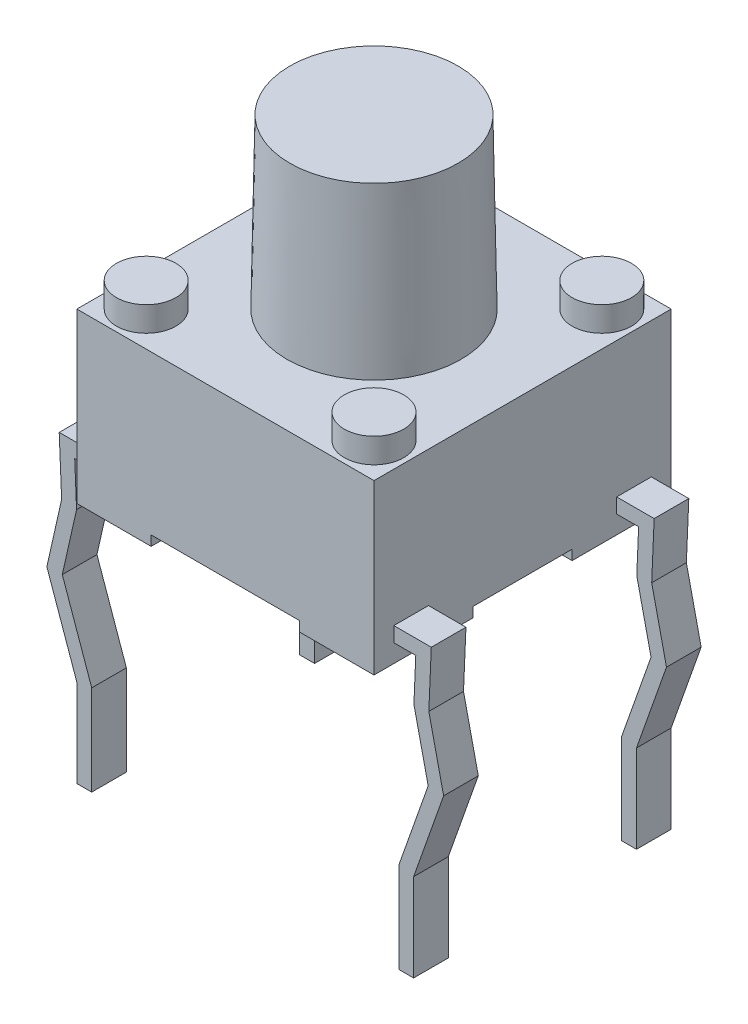
SolidWorks part; units mm, degrees
ref_plane "Ön Düzlem" through (0, 0, 0) normal (0, 0, 1) x (1, 0, 0)
ref_plane "Üst Düzlem" through (0, 0, 0) normal (0, 1, 0) x (1, 0, 0)
ref_plane "Sağ Düzlem" through (0, 0, 0) normal (1, 0, 0) x (0, 0, -1)
sketch "Çizim1" plane through (0, 0, 0) normal (0, 1, 0) x (1, 0, 0)
  line L1 (3, 3) -> (-3, 3)
  line L2 (3, 3) -> (3, -3)
  line L3 (3, -3) -> (-3, -3)
  line L4 (-3, 3) -> (-3, -3)
  line L5 (3, 3) -> (-3, -3) construction
  line L6 (3, -3) -> (-3, 3) construction
  point P0 (0, 0)
  dimension "D1" = 6
  dimension "D2" = 6
extrude "Yükseklik-Ekstrüzyon1" add sketch "Çizim1" against normal blind 3.3
sketch "Çizim2" plane through (0, 0, 0) normal (0, 1, 0) x (1, 0, 0)
  line L0 (-3, -3) -> (3, -3) construction
  line L1 (3, -3) -> (3, 3) construction
  line L2 (3, 3) -> (-3, 3) construction
  line L3 (-3, 3) -> (-3, -3) construction
  line L4 (-3, -3) -> (3, -3)
  line L5 (3, -3) -> (3, 3)
  line L6 (3, 3) -> (-3, 3)
  line L7 (-3, 3) -> (-3, -3)
extrude "Yükseklik-Ekstrüzyon2" add sketch "Çizim2" along normal blind 0.1
sketch "Çizim3" plane through (0, 0, 3) normal (0, 0, 1) x (1, 0, 0)
  line L0 (0, 0.1) -> (0, -3.3) construction
  line L1 (-3, 0.1) -> (3, 0.1) construction
  line L2 (-3, -3.3) -> (3, -3.3) construction
  line L3 (1.5, -3.1) -> (-1.5, -3.1)
  line L4 (-1.5, -3.1) -> (-1.5, -3.3)
  line L5 (-1.5, -3.3) -> (1.5, -3.3)
  line L6 (1.5, -3.3) -> (1.5, -3.1)
  point P9 (0, -3.1)
  dimension "D1" = 3
  dimension "D2" = 0.2
extrude "Kes-Ekstrüzyon1" cut sketch "Çizim3" against normal blind 1.5
mirror "Aynalama1" about plane through (0, 0, 0) normal (0, 0, 1) of "Kes-Ekstrüzyon1"
sketch "Çizim4" plane through (-3, 0, 0) normal (-1, 0, 0) x (0, 0, 1)
  line L0 (0, 0.1) -> (0, -3.3) construction
  line L1 (-3, 0.1) -> (3, 0.1) construction
  line L2 (-3, -3.3) -> (3, -3.3) construction
  line L3 (1, -3.1) -> (-1, -3.1)
  line L4 (-1, -3.1) -> (-1, -3.3)
  line L5 (-1, -3.3) -> (1, -3.3)
  line L6 (1, -3.3) -> (1, -3.1)
  point P9 (0, -3.1)
  dimension "D1" = 2
  dimension "D2" = 0.2
extrude "Kes-Ekstrüzyon2" cut sketch "Çizim4" against normal through all
sketch "Çizim5" plane through (0, 0.1, 0) normal (0, 1, 0) x (1, 0, 0)
  circle A0 centre (0, 0) radius 1.7
  dimension "D1" = 3.4
extrude "Yükseklik-Ekstrüzyon3" add sketch "Çizim5" along normal blind 3.4
draft "Draft4" type of draft neutral plane draft angle 1 faces to draft 1 face at (0, 3.5, 1.7) neutral plane through (0, 3.5, 0) neutral plane normal (0, 1, 0) parameters "D1"=1
sketch "Çizim6" plane through (0, 0.1, 0) normal (0, 1, 0) x (1, 0, 0)
  line L0 (0, 3) -> (0, -3) construction
  line L1 (3, 3) -> (-3, 3) construction
  line L2 (-3, -3) -> (3, -3) construction
  line L3 (-3, 0) -> (3, 0) construction
  line L4 (-3, 3) -> (-3, -3) construction
  line L5 (3, -3) -> (3, 3) construction
  circle A0 centre (-2.3, 2.3) radius 0.6
  circle A1 centre (2.3, 2.3) radius 0.6
  circle A2 centre (2.3, -2.3) radius 0.6
  circle A3 centre (-2.3, -2.3) radius 0.6
  dimension "D1" = 1.2
  dimension "D2" = 0.7
  dimension "D3" = 0.7
extrude "Yükseklik-Ekstrüzyon4" add sketch "Çizim6" along normal blind 0.5
ref_plane "Düzlem1" through (0, 0, 2.25) normal (0, 0, 1) x (1, 0, 0)
sketch "Çizim8" plane through (0, 0, 2.25) normal (0, 0, 1) x (1, 0, 0)
  line L0 (-3, -2.7851) -> (-3.6, -2.7851) construction
  line L1 (-3, -3.3) -> (-3, 0.1) construction
  line L2 (-3.6, -2.7851) -> (-3.5565, -3.7961) construction
  line L3 (-3.5565, -3.7961) -> (-3.85, -5.1) construction
  line L4 (-3.85, -5.1) -> (-3.25, -6.8) construction
  line L5 (-3.25, -6.8) -> (-3.25, -8.5979) construction
  line L6 (0, 0) -> (0, -10.9277) construction
  line L7 (3.25, -6.8) -> (3.25, -8.5979) construction
  line L8 (3.85, -5.1) -> (3.25, -6.8) construction
  line L9 (3.5565, -3.7961) -> (3.85, -5.1) construction
  line L10 (3.6, -2.7851) -> (3.5565, -3.7961) construction
  line L11 (3, -2.7851) -> (3.6, -2.7851) construction
  line L12 (-3, -3.3) -> (-1.5, -3.3) construction
  line L13 (1.5, -3.3) -> (3, -3.3) construction
  line L14 (-3, -2.6351) -> (-3.7566, -2.6351)
  line L15 (-3.7566, -2.6351) -> (-3.7073, -3.7826)
  line L16 (-3.7073, -3.7826) -> (-4.0058, -5.1092)
  line L17 (-4.0058, -5.1092) -> (-3.4, -6.8257)
  line L18 (-3.4, -6.8257) -> (-3.4, -8.5979)
  line L19 (3, -2.9351) -> (3.4434, -2.9351)
  line L20 (3.4434, -2.9351) -> (3.4058, -3.8095)
  line L21 (3.4058, -3.8095) -> (3.6942, -5.0908)
  line L22 (3.6942, -5.0908) -> (3.1, -6.7743)
  line L23 (3.1, -6.7743) -> (3.1, -8.5979)
  line L24 (-3, -2.9351) -> (-3.4434, -2.9351)
  line L25 (-3.4434, -2.9351) -> (-3.4058, -3.8095)
  line L26 (-3.4058, -3.8095) -> (-3.6942, -5.0908)
  line L27 (-3.6942, -5.0908) -> (-3.1, -6.7743)
  line L28 (-3.1, -6.7743) -> (-3.1, -8.5979)
  line L29 (3, -2.6351) -> (3.7566, -2.6351)
  line L30 (3.7566, -2.6351) -> (3.7073, -3.7826)
  line L31 (3.7073, -3.7826) -> (4.0058, -5.1092)
  line L32 (4.0058, -5.1092) -> (3.4, -6.8257)
  line L33 (3.4, -6.8257) -> (3.4, -8.5979)
  line L34 (-3.4, -8.5979) -> (-3.1, -8.5979)
  line L35 (3.1, -8.5979) -> (3.4, -8.5979)
  line L36 (-3, -2.6351) -> (-3, -2.9351)
  line L37 (3, -2.6351) -> (3, -2.9351)
  dimension "D1" = 6.5
  dimension "D2" = 0.6
  dimension "D3" = 3.5
  dimension "D4" = 7.7
  dimension "D5" = 1.8
  dimension "D6" = 0.15
  dimension "D7" = 0.15
extrude "Yükseklik-Ekstrüzyon5" add sketch "Çizim8" along normal blind 0.35 and the other way blind 0.35
pattern_linear "LÇoğaltma1" count 2 spacing 4.5 along (0, 0, -1) of "Yükseklik-Ekstrüzyon5"
